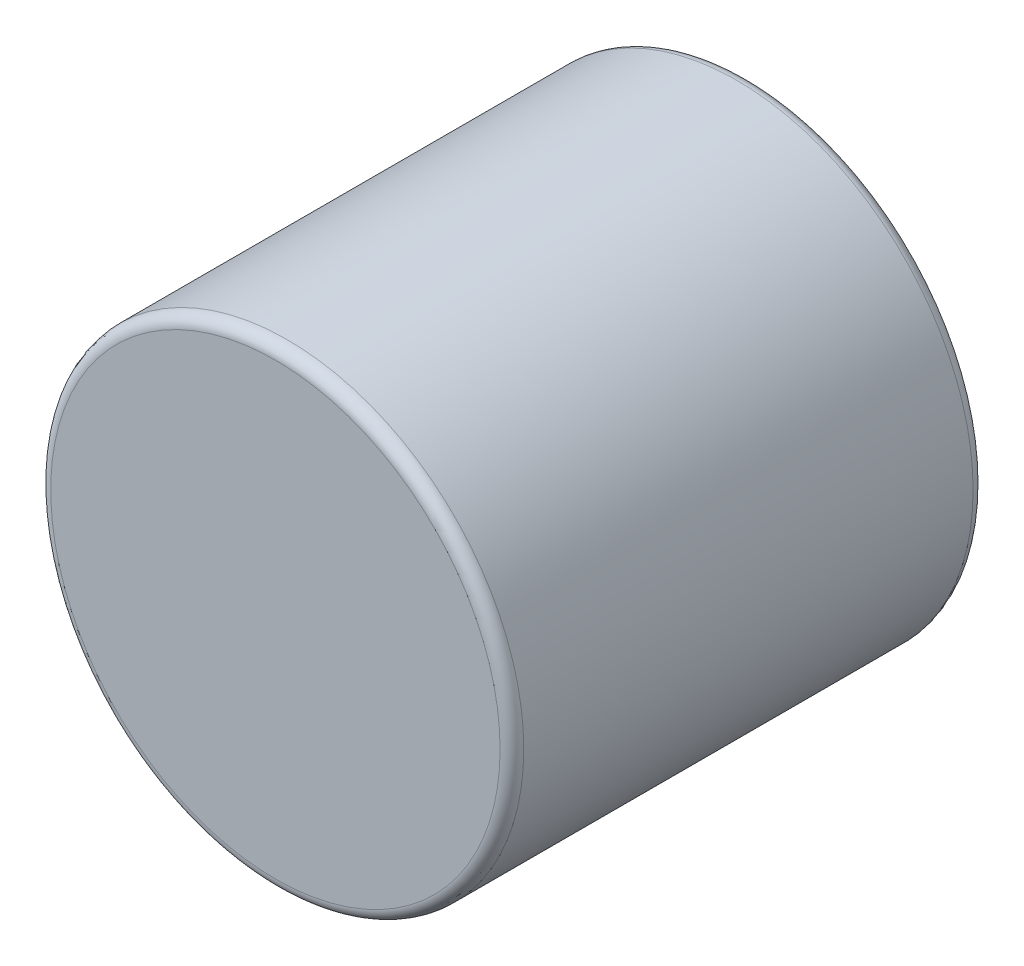
SolidWorks part; units mm, degrees
material "Nickel"
ref_plane "Front Plane" through (0, 0, 0) normal (0, 0, 1) x (1, 0, 0)
ref_plane "Top Plane" through (0, 0, 0) normal (0, 1, 0) x (1, 0, 0)
ref_plane "Right Plane" through (0, 0, 0) normal (1, 0, 0) x (0, 0, -1)
sketch "Sketch1" plane through (0, 0, 0) normal (0, 0, 1) x (1, 0, 0)
  circle A0 centre (0, 0) radius 3.175 construction
  dimension "OD" = 6.35
sketch "Sketch2" plane through (0, 0, 0) normal (1, 0, 0) x (0, 0, -1)
  line L0 (-3.175, 0) -> (3.175, 0) construction
  line L1 (0, 3.175) -> (0, -3.175) construction
  line L3 (-3.175, 3.175) -> (3.175, 3.175)
  line L4 (-3.175, 3.175) -> (-3.175, -3.175)
  line L5 (-3.175, -3.175) -> (3.175, -3.175)
  line L6 (3.175, 3.175) -> (3.175, -3.175)
  point P4 (0, 0)
  point P12 (0, 3.175)
  dimension "Thickness" = 6.35
sketch "Sketch3" plane through (0, 0, 0) normal (0, 0, 1) x (1, 0, 0)
  circle A0 centre (0, 0) radius 3.175 construction
  circle A1 centre (0, 0) radius 3.175
extrude "Boss-Extrude1" add sketch "Sketch3" along normal up to vertex (3.175 mm away) and the other way up to vertex (3.175 mm away) up to point (0, 3.175, 3.175) other way up to point (0, 3.175, -3.175)
fillet "Fillet1" radius 0.1588 2 edges at (3.175, 0, -3.175) (3.175, 0, 3.175)
equation "\"Fillet@Fillet1\"=\"Thickness@Sketch2\"*.025"
